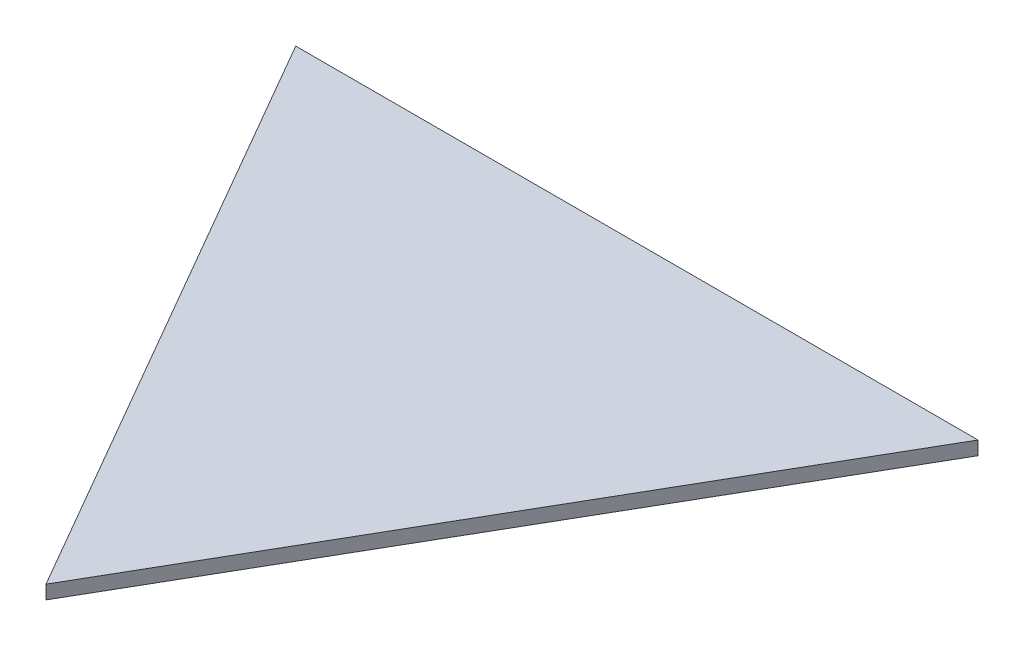
SolidWorks part; units mm, degrees
ref_plane "Front Plane" through (0, 0, 0) normal (0, 0, 1) x (1, 0, 0)
ref_plane "Top Plane" through (0, 0, 0) normal (0, 1, 0) x (1, 0, 0)
ref_plane "Right Plane" through (0, 0, 0) normal (1, 0, 0) x (0, 0, -1)
sketch "Sketch1" plane through (0, 0, 0) normal (0, 1, 0) x (1, 0, 0)
  line L0 (0, 0) -> (-250, 433.0127)
  line L1 (-250, 433.0127) -> (250, 433.0127)
  line L2 (250, 433.0127) -> (0, 0)
  dimension "D1" = 500
extrude "Boss-Extrude1" add sketch "Sketch1" along normal blind 10
ref_point "Point1"
ref_point "Point2"
ref_point "Point3"
